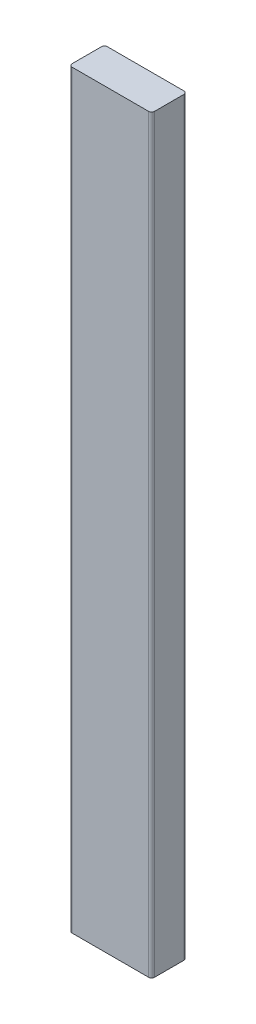
SolidWorks part; units mm, degrees
ref_plane "Front" through (0, 0, 0) normal (0, 0, 1) x (1, 0, 0)
ref_plane "Top" through (0, 0, 0) normal (0, 1, 0) x (1, 0, 0)
ref_plane "Right" through (0, 0, 0) normal (1, 0, 0) x (0, 0, -1)
sketch "Sketch1" plane through (0, 0, 0) normal (0, 1, 0) x (1, 0, 0)
  line L1 (44.45, 19.05) -> (-44.45, 19.05)
  line L2 (44.45, 19.05) -> (44.45, -19.05)
  line L3 (44.45, -19.05) -> (-44.45, -19.05)
  line L4 (-44.45, 19.05) -> (-44.45, -19.05)
  line L5 (44.45, 19.05) -> (-44.45, -19.05) construction
  line L6 (44.45, -19.05) -> (-44.45, 19.05) construction
  point P0 (0, 0)
  dimension "D1" = 88.9
  dimension "D2" = 38.1
extrude "Boss-Extrude1" add sketch "Sketch1" along normal blind 808.0375
fillet "Fillet1" radius 3.175 4 edges at (-44.45, 404.0187, -19.05) (-44.45, 404.0187, 19.05) (44.45, 404.0187, -19.05) (44.45, 404.0187, 19.05)
